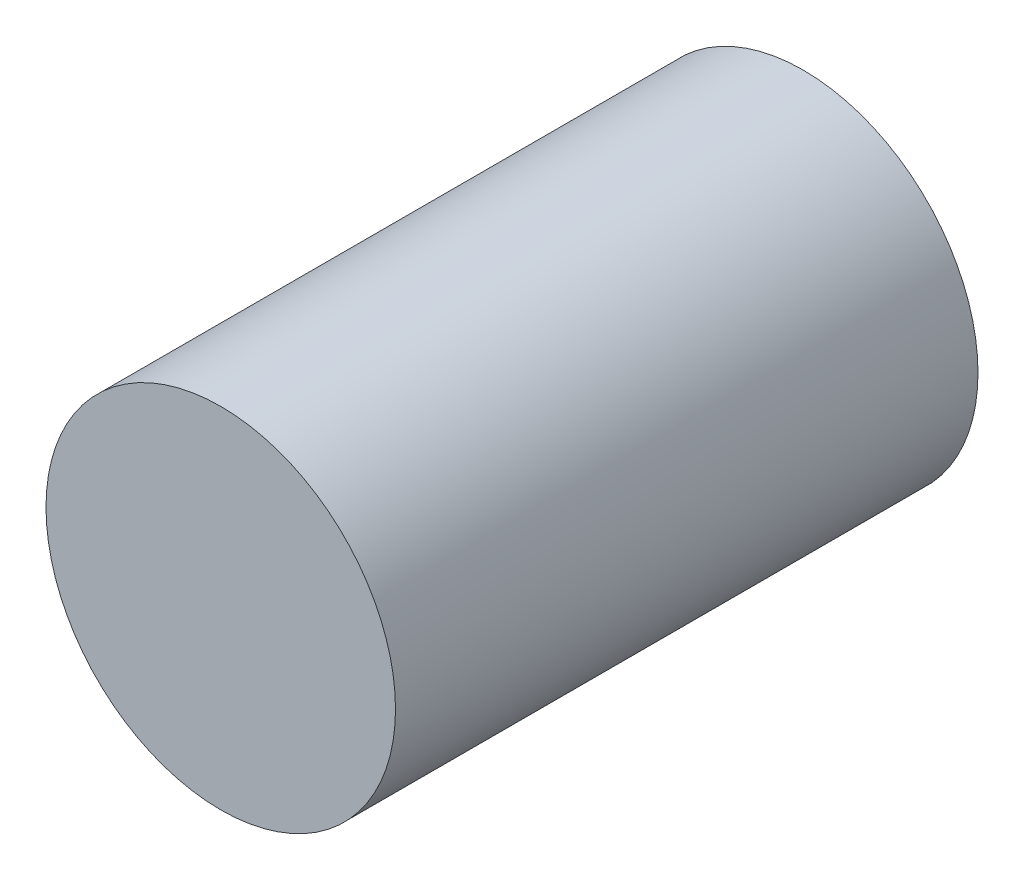
SolidWorks part; units mm, degrees
material "Brass"
ref_plane "Front Plane" through (0, 0, 0) normal (0, 0, 1) x (1, 0, 0)
ref_plane "Top Plane" through (0, 0, 0) normal (0, 1, 0) x (1, 0, 0)
ref_plane "Right Plane" through (0, 0, 0) normal (1, 0, 0) x (0, 0, -1)
sketch "Sketch1" plane through (0, 0, 0) normal (0, 0, 1) x (1, 0, 0)
  circle A0 centre (0, 0) radius 3
  circle A1 centre (0, 0) radius 1.75
  dimension "D1" = 6
  dimension "D2" = 3.5
extrude "Boss-Extrude1" add sketch "Sketch1" along normal blind 10 contours A0
sketch "Sketch2" plane through (0, 0, 0) normal (0, 0, 1) x (1, 0, 0)
  circle A0 centre (0, 0) radius 3
  circle A1 centre (0, 0) radius 1.75
extrude "Cut-Extrude1" cut sketch "Sketch2" along normal blind 0.5
ref_plane "Plane1" through (0, 0, 4) normal (0, 0, 1) x (1, 0, 0)
sketch "Sketch3" plane through (0, 0, 0.5) normal (0, 0, -1) x (-1, 0, 0)
  circle A0 centre (0, 0) radius 1.75 construction
  circle A1 centre (0, 0) radius 1.75
extrude "Boss-Extrude2" add sketch "Sketch3" along normal blind 0.1
